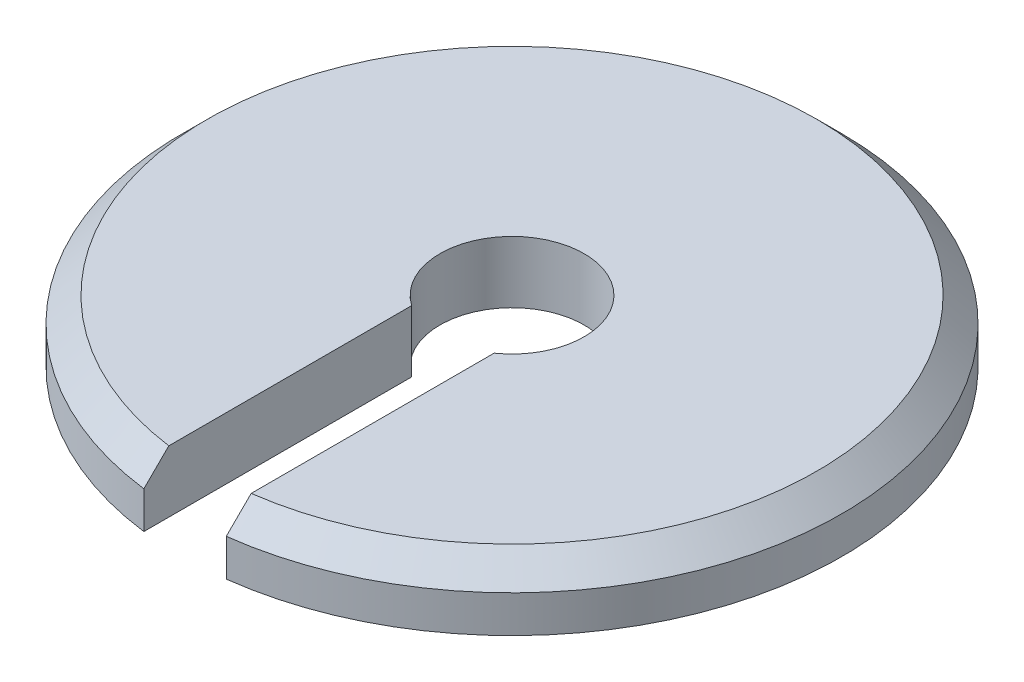
SolidWorks part; units mm, degrees
ref_plane "Front Plane" through (0, 0, 0) normal (0, 0, 1) x (1, 0, 0)
ref_plane "Top Plane" through (0, 0, 0) normal (0, 1, 0) x (1, 0, 0)
ref_plane "Right Plane" through (0, 0, 0) normal (1, 0, 0) x (0, 0, -1)
sketch "Sketch1" plane through (0, 0, 0) normal (0, 1, 0) x (1, 0, 0)
  line L1 (-1.27, -11.7375) -> (1.27, -11.7375)
  line L2 (-1.27, -11.7375) -> (-1.27, -0.5108)
  line L3 (-1.27, -0.5108) -> (1.27, -0.5108)
  line L4 (1.27, -11.7375) -> (1.27, -0.5108)
  line L5 (-1.27, -11.7375) -> (1.27, -0.5108) construction
  line L6 (-1.27, -0.5108) -> (1.27, -11.7375) construction
  circle A0 centre (0, 0) radius 10.16
  circle A1 centre (0, 0) radius 2.2225
  point P4 (0, -6.1241)
  point P9 (0, 0)
  dimension "D1" = 20.32
  dimension "D2" = 4.445
  dimension "D3" = 2.54
extrude "Boss-Extrude1" add sketch "Sketch1" along normal blind 1.905 contours A1 L4 A0 L2
chamfer "Chamfer1" distance 0.762 angle 45 1 edges at (0, 1.905, -10.16)
